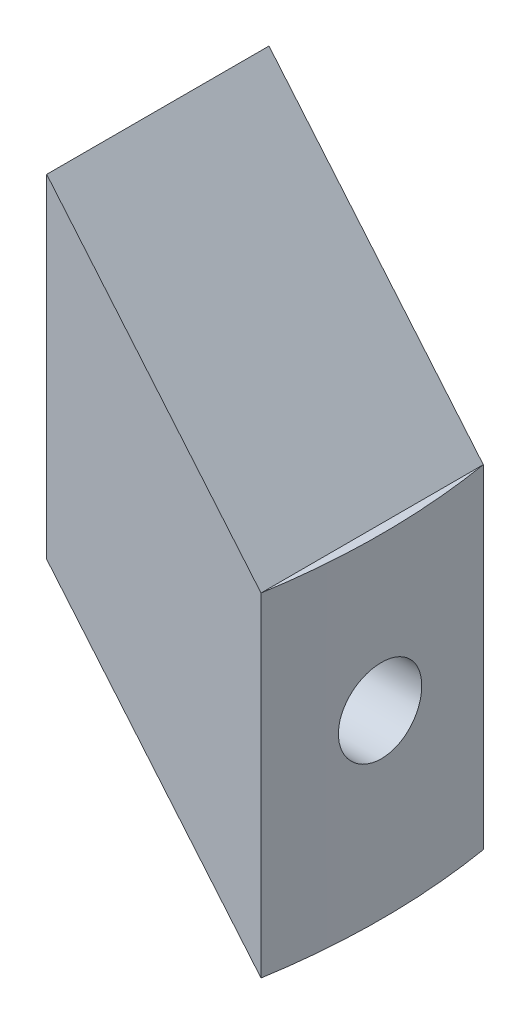
SolidWorks part; units mm, degrees
ref_plane "Front Plane" through (0, 0, 0) normal (0, 0, 1) x (1, 0, 0)
ref_plane "Top Plane" through (0, 0, 0) normal (0, 1, 0) x (1, 0, 0)
ref_plane "Right Plane" through (0, 0, 0) normal (1, 0, 0) x (0, 0, -1)
sketch "Sketch5" plane through (0, 0, 0) normal (0, 0, 1) x (1, 0, 0)
  line L0 (-51.5908, 0) -> (51.5908, 0) construction
  line L1 (0, -34.616) -> (0, 34.616) construction
  line L2 (0, -19.05) -> (0, 19.05)
  line L3 (0, 19.05) -> (-24.4902, 48.2363)
  line L4 (-24.4902, 48.2363) -> (-24.4902, 10.1363)
  line L5 (0, -19.05) -> (-24.4902, 10.1363)
  point P4 (0, 0)
  point P8 (0, 0)
  point P11 (0, 0)
  dimension "D1" = 38.1
  dimension "D2" = 40
  dimension "D3" = 38.1
  dimension "D4" = 38.1
extrude "Boss-Extrude4" add sketch "Sketch5" along normal mid plane 25.4
sketch "Sketch6" plane through (0, 0, 0) normal (0, 1, 0) x (1, 0, 0)
  line L0 (-54.4822, 0) -> (54.4822, 0) construction
  line L1 (0, -47.5243) -> (0, 47.5243) construction
  line L6 (0, 12.7) -> (0, -12.7)
  line L7 (-76.2, -40.3489) -> (-76.2, 40.3489) construction
  arc A0 (0, -12.7) -> (0, 12.7) centre (-76.2, 0) ccw
  point P4 (0, 0)
  point P8 (0, 0)
  point P21 (-76.2, 0)
  dimension "D1" = 76.2
extrude "Boss-Extrude5" add sketch "Sketch6" along normal mid plane 38.1
sketch "Sketch7" plane through (0, 0, 0) normal (0, 0, 1) x (1, 0, 0)
  line L0 (-57.4059, 0) -> (57.4059, 0) construction
  line L2 (0, -42.4061) -> (0, 42.4061) construction
  line L3 (1.0511, -50.5562) -> (1.0511, 50.5562) construction
  line L5 (1.0511, 19.05) -> (0, 19.05) construction
  line L6 (1.0511, -3.175) -> (-11.6489, -3.175) construction
  line L11 (1.0511, 0) -> (0, 1.1118) construction
  line L12 (1.0511, 0) -> (0, -1.1118) construction
  line L14 (1.0511, 6.35) -> (-11.6489, 6.35)
  line L15 (-11.6489, -3.175) -> (-11.6489, 6.35) construction
  line L16 (1.0511, 1.5875) -> (-11.6489, 6.35) construction
  line L17 (1.0511, 1.5875) -> (-11.6489, -3.175) construction
  line L18 (1.0511, 6.35) -> (1.0511, -3.175) construction
  line L19 (-31.4556, 1.5875) -> (33.5578, 1.5875) construction
  line L20 (-11.6489, 1.5875) -> (-11.6489, 6.35)
  line L21 (-11.6489, 1.5875) -> (1.0511, 1.5875)
  line L22 (1.0511, 1.5875) -> (1.0511, 6.35)
  point P0 (1.0511, 1.5875)
  point P4 (0, 0)
  point P8 (0, 0)
  point P11 (1.0511, 0)
  point P13 (1.0511, 0)
  point P25 (1.0511, 1.5875)
  dimension "D1" = 9.525
  dimension "D2" = 12.7
  dimension "D3" = 12.7
revolve "Cut-Revolve5" cut sketch "Sketch7" angle 360 about L19
